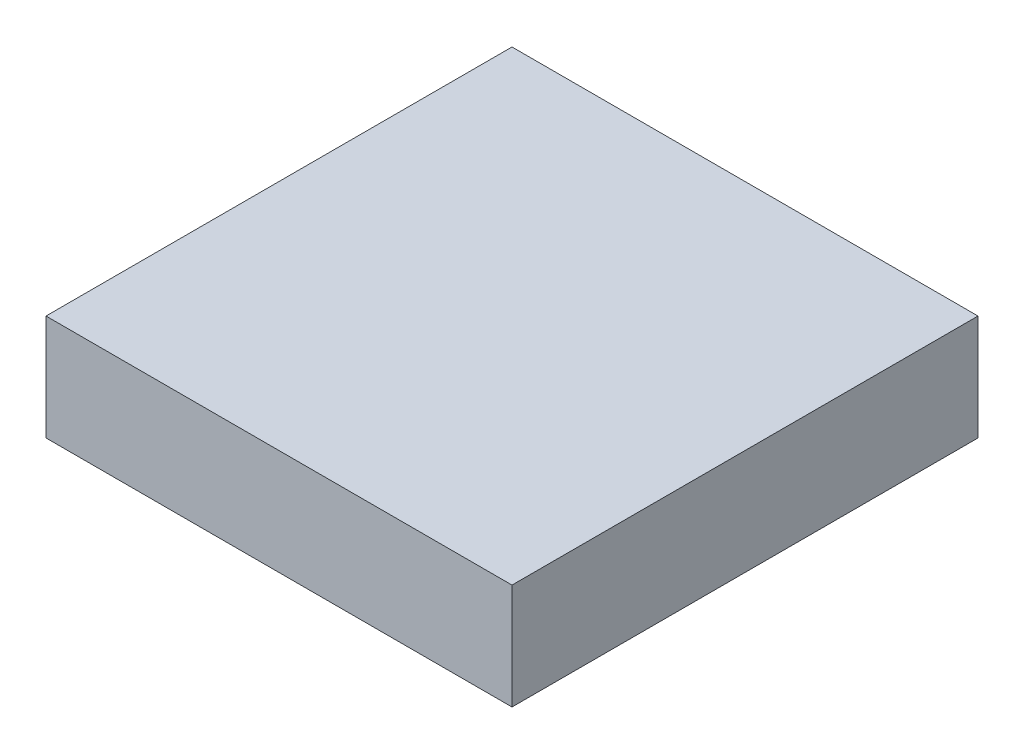
SolidWorks part; units mm, degrees
ref_plane "Front Plane" through (0, 0, 0) normal (0, 0, 1) x (1, 0, 0)
ref_plane "Top Plane" through (0, 0, 0) normal (0, 1, 0) x (1, 0, 0)
ref_plane "Right Plane" through (0, 0, 0) normal (1, 0, 0) x (0, 0, -1)
sketch "Sketch1" plane through (0, 0, 0) normal (1, 0, 0) x (0, 0, -1)
  line L1 (0, 0) -> (150, 0)
  line L2 (0, 0) -> (0, -34)
  line L3 (0, -34) -> (150, -34)
  line L4 (150, 0) -> (150, -34)
  dimension "D1" = 34
  dimension "D2" = 150
extrude "Boss-Extrude1" add sketch "Sketch1" along normal blind 150
